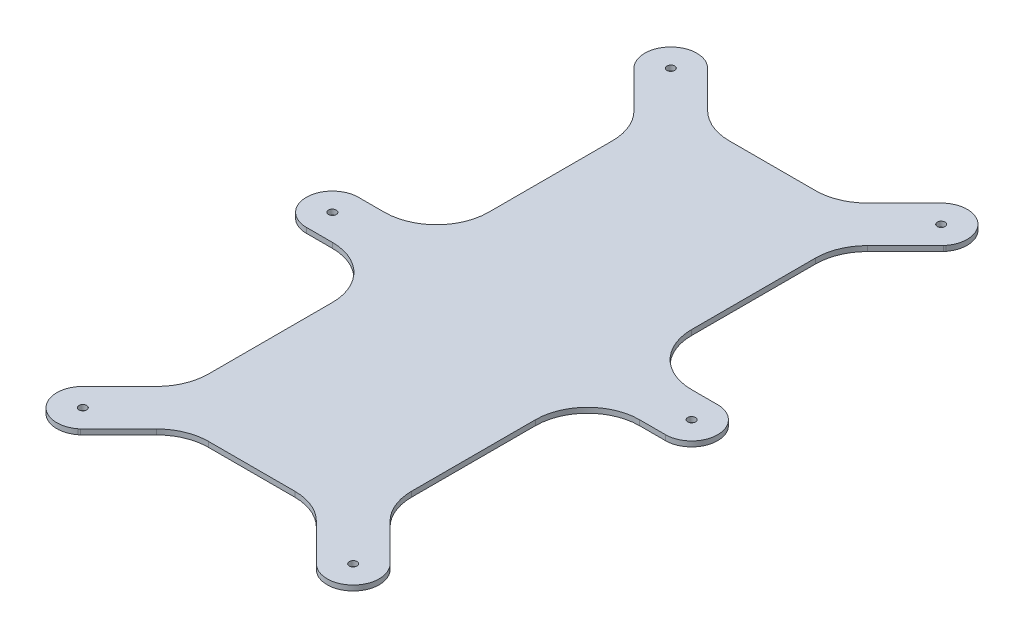
SolidWorks part; units mm, degrees
ref_plane "前视基准面" through (0, 0, 0) normal (0, 0, 1) x (1, 0, 0)
ref_plane "上视基准面" through (0, 0, 0) normal (0, 1, 0) x (1, 0, 0)
ref_plane "右视基准面" through (0, 0, 0) normal (1, 0, 0) x (0, 0, -1)
sketch "草图2" plane through (0, 0, 0) normal (0, 1, 0) x (1, 0, 0)
  line L0 (-69, -10) -> (-59, -10)
  line L1 (12.1414, -100) -> (-12.1414, -100)
  line L2 (39, -73.1414) -> (39, -30)
  line L3 (12.1414, 100) -> (-12.1414, 100)
  line L4 (-39, -73.1414) -> (-39, -30)
  line L6 (-43.209, 85.4152) -> (-59.8244, 106.7921)
  line L7 (24.4152, 104.209) -> (45.7921, 120.8244)
  line L8 (43.209, 85.4152) -> (59.8244, 106.7921)
  line L9 (-24.4152, 104.209) -> (-45.7921, 120.8244)
  line L10 (43.209, -85.4152) -> (59.8244, -106.7921)
  line L11 (24.4152, -104.209) -> (45.7921, -120.8244)
  line L12 (-43.209, -85.4152) -> (-59.8244, -106.7921)
  line L13 (-24.4152, -104.209) -> (-45.7921, -120.8244)
  line L14 (-69, 10) -> (-59, 10)
  line L15 (69, 10) -> (59, 10)
  line L16 (69, -10) -> (59, -10)
  line L17 (39, 30) -> (39, 73.1414)
  line L18 (-39, 30) -> (-39, 73.1414)
  arc A0 (59.8244, 106.7921) -> (45.7921, 120.8244) centre (51.9289, 112.9289) ccw
  arc A1 (-59.8244, 106.7921) -> (-45.7921, 120.8244) centre (-51.9289, 112.9289) cw
  arc A2 (59.8244, -106.7921) -> (45.7921, -120.8244) centre (51.9289, -112.9289) cw
  arc A3 (-59.8244, -106.7921) -> (-45.7921, -120.8244) centre (-51.9289, -112.9289) ccw
  arc A4 (69, -10) -> (69, 10) centre (69, 0) ccw
  arc A5 (-69, -10) -> (-69, 10) centre (-69, 0) cw
  arc A6 (39, -30) -> (59, -10) centre (59, -30) cw
  arc A7 (39, 30) -> (59, 10) centre (59, 30) ccw
  arc A8 (-39, -30) -> (-59, -10) centre (-59, -30) ccw
  arc A9 (-59, 10) -> (-39, 30) centre (-59, 30) ccw
  arc A10 (39, 73.1414) -> (43.209, 85.4152) centre (59, 73.1414) cw
  arc A11 (-39, 73.1414) -> (-43.209, 85.4152) centre (-59, 73.1414) ccw
  arc A12 (-43.209, -85.4152) -> (-39, -73.1414) centre (-59, -73.1414) ccw
  arc A13 (39, -73.1414) -> (43.209, -85.4152) centre (59, -73.1414) ccw
  arc A14 (24.4152, -104.209) -> (12.1414, -100) centre (12.1414, -120) ccw
  arc A15 (-24.4152, -104.209) -> (-12.1414, -100) centre (-12.1414, -120) cw
  arc A16 (12.1414, 100) -> (24.4152, 104.209) centre (12.1414, 120) ccw
  arc A17 (-12.1414, 100) -> (-24.4152, 104.209) centre (-12.1414, 120) cw
  point P0 (0, 0)
  point P5 (59, 120)
  point P6 (19, 100)
  point P8 (39, 80)
  point P10 (79, 0)
  point P40 (39, -10)
  point P43 (39, 10)
  point P46 (-39, -10)
  point P49 (-39, 10)
  point P50 (39, 80)
  point P53 (-39, 80)
  point P56 (-39, -80)
  point P65 (19, 100)
  dimension "D7" = 20
  dimension "D10" = 20
  dimension "D11" = 20
  dimension "D6" = 20
  dimension "D1" = 20
  dimension "D2" = 20
  dimension "D3" = 20
  dimension "D4" = 20
  dimension "D5" = 160
  dimension "D8" = 103.8579
  dimension "D9" = 225.8579
extrude "凸台-拉伸1" add sketch "草图2" along normal blind 2
sketch "草图3" plane through (0, 2, 0) normal (0, 1, 0) x (1, 0, 0)
  line L0 (59, 120) -> (6.176, 67.176) construction
  line L1 (12.1414, 100) -> (-12.1414, 100) construction
  line L2 (24.8579, 100) -> (12.1414, 100)
  line L3 (24.8579, 100) -> (45.2992, 120.4414)
  line L4 (0, 100) -> (19.5, 80.5) construction
  line L5 (19.5, 80.5) -> (39, 61) construction
  line L6 (39, 30) -> (39, 73.1414) construction
  line L7 (45.7921, 120.8244) -> (24.4152, 104.209) construction
  line L8 (12.1414, 100) -> (45.2992, 120.4414)
  line L9 (39, 73.1414) -> (59.4414, 106.2992)
  line L10 (39, 85.8579) -> (59.4414, 106.2992)
  line L11 (39, 85.8579) -> (39, 73.1414)
  arc A0 (59.8244, 106.7921) -> (45.7921, 120.8244) centre (51.9289, 112.9289) ccw construction
  point P0 (24.8579, 100)
  dimension "D1" = 10
extrude "切除-拉伸1" cut sketch "草图3" against normal through all
mirror "镜向1" about plane through (0, 0, 0) normal (0, 0, 1) of "切除-拉伸1"
mirror "镜向2" about plane through (0, 0, 0) normal (1, 0, 0) of "切除-拉伸1", "镜向1"
fillet "圆角1" radius 20 8 edges at (-39, 1, 85.8579) (-24.8579, 1, 100) (24.8579, 1, 100) (39, 1, 85.8579) (39, 1, -85.8579) (24.8579, 1, -100) (-24.8579, 1, -100) (-39, 1, -85.8579)
sketch "草图4" plane through (0, 2, 0) normal (0, 1, 0) x (1, 0, 0)
  line L0 (30.7157, 105.8579) -> (45.2992, 120.4414) construction
  line L2 (59.4414, 106.2992) -> (44.8579, 91.7157) construction
  line L4 (0, 100) -> (0, -100) construction
  line L5 (16.5736, 100) -> (-16.5736, 100) construction
  line L6 (59, 120) -> (37.3405, 98.3405) construction
  line L9 (-16.5736, -100) -> (16.5736, -100) construction
  line L10 (-79, 0) -> (79, 0) construction
  circle A0 centre (69, 0) radius 1.5
  arc A1 (69, -10) -> (69, 10) centre (69, 0) ccw construction
  circle A2 centre (51.9289, 112.9289) radius 1.5
  arc A3 (-69, 10) -> (-69, -10) centre (-69, 0) ccw construction
  arc A4 (59.8244, 106.7921) -> (45.7921, 120.8244) centre (51.9289, 112.9289) ccw construction
  circle A5 centre (51.9289, -112.9289) radius 1.5
  circle A6 centre (-69, 0) radius 1.5
  circle A7 centre (-51.9289, 112.9289) radius 1.5
  circle A8 centre (-51.9289, -112.9289) radius 1.5
  point P35 (59, 0)
  point P36 (0, 0)
  point P37 (0, 0)
  dimension "D1" = 3
  dimension "D3" = 3
  dimension "D2" = 10
  dimension "D4" = 10
extrude "切除-拉伸2" cut sketch "草图4" against normal through all
